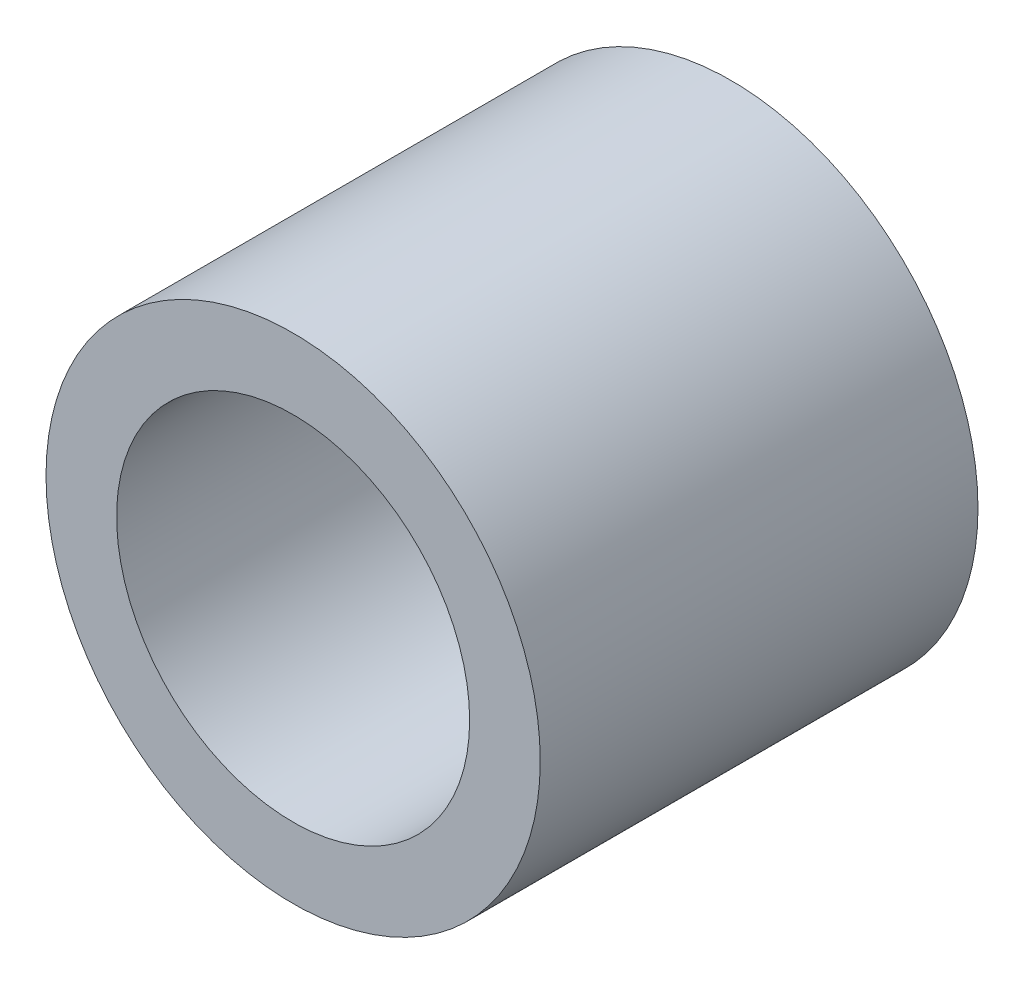
SolidWorks part; units mm, degrees
ref_plane "Front Plane" through (0, 0, 0) normal (0, 0, 1) x (1, 0, 0)
ref_plane "Top Plane" through (0, 0, 0) normal (0, 1, 0) x (1, 0, 0)
ref_plane "Right Plane" through (0, 0, 0) normal (1, 0, 0) x (0, 0, -1)
sketch "Sketch2" plane through (0, 0, 0) normal (0, 0, 1) x (1, 0, 0)
  circle A0 centre (0, 0) radius 12.5
  circle A1 centre (0, 0) radius 17.5
extrude "Boss-Extrude1" add sketch "Sketch2" along normal blind 31
